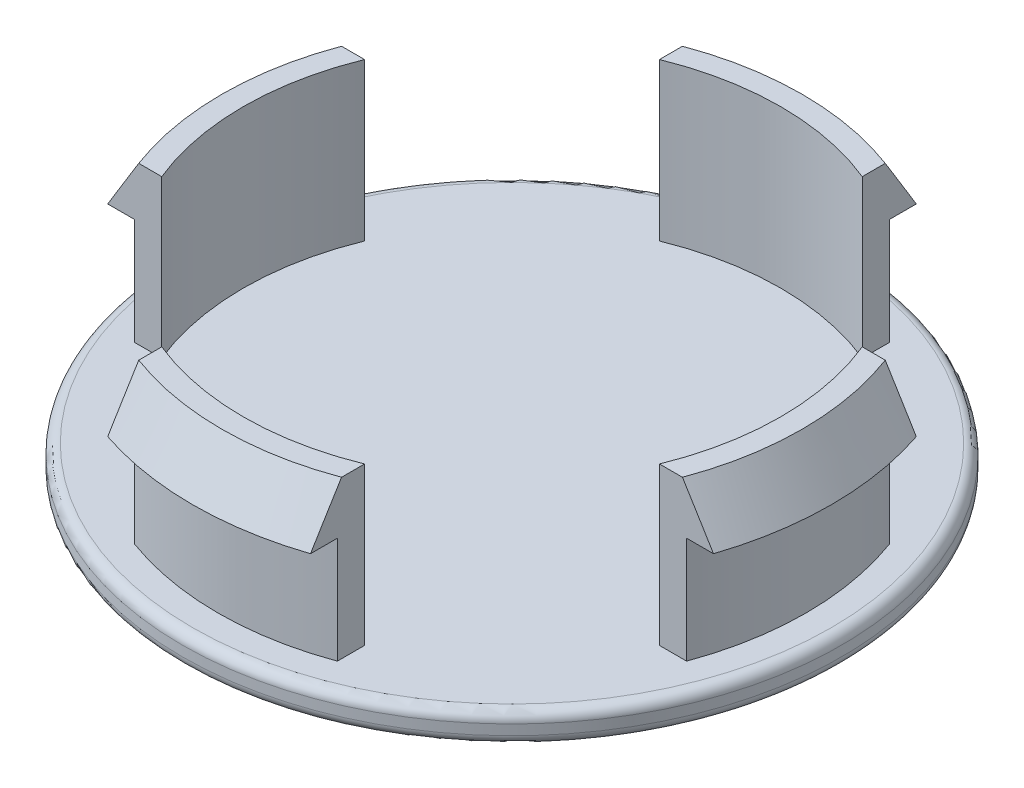
SolidWorks part; units mm, degrees
ref_plane "Спереди" through (0, 0, 0) normal (0, 0, 1) x (1, 0, 0)
ref_plane "Сверху" through (0, 0, 0) normal (0, 1, 0) x (1, 0, 0)
ref_plane "Справа" through (0, 0, 0) normal (1, 0, 0) x (0, 0, -1)
sketch "Эскиз3" plane through (0, 0, 0) normal (0, 0, 1) x (1, 0, 0)
  line L0 (0, 0) -> (0, 58.4773)
sketch "Эскиз1" plane through (0, 0, 0) normal (0, 0, 1) x (1, 0, 0)
  line L0 (0, 0) -> (0, -17.5509) construction
  line L1 (0, 0) -> (-31.5, 0)
  line L2 (-32.5, 1) -> (-32.5, 2)
  line L3 (-31.5, 3) -> (-29, 3)
  line L4 (-29, 3) -> (-29, 13.5)
  line L5 (-29, 13.5) -> (-31.5, 13.5)
  line L6 (-31.5, 13.5) -> (-28.6132, 18.5)
  line L7 (-28.6132, 18.5) -> (-26.5, 18.5)
  line L8 (-26.5, 18.5) -> (-26.5, 3)
  line L9 (-26.5, 3) -> (0, 3)
  line L10 (0, 3) -> (0, 0)
  arc A0 (-32.5, 1) -> (-31.5, 0) centre (-31.5, 1) ccw
  arc A1 (-32.5, 2) -> (-31.5, 3) centre (-31.5, 2) cw
  dimension "D10" = 1
  dimension "D11" = 1
  dimension "D1" = 65
  dimension "D2" = 58
  dimension "D3" = 63
  dimension "D4" = 3
  dimension "D5" = 3
  dimension "D6" = 5
  dimension "D7" = 5
  dimension "D8" = 10.5
  dimension "D9" = 60
revolve "Повернуть1" add sketch "Эскиз1" angle 360 about L0
sketch "Эскиз2" plane through (0, 18.5, 0) normal (0, 1, 0) x (1, 0, 0)
  line L0 (0, 0) -> (0, 37.57) construction
  line L1 (-10, 40.8566) -> (-10, 14.3515)
  line L2 (10, 40.8566) -> (10, 14.3515)
  line L3 (40.8566, 10) -> (14.3515, 10)
  line L4 (40.8566, -10) -> (14.3515, -10)
  line L5 (10, -40.8566) -> (10, -14.3515)
  line L6 (-10, -40.8566) -> (-10, -14.3515)
  line L7 (-40.8566, -10) -> (-14.3515, -10)
  line L8 (-40.8566, 10) -> (-14.3515, 10)
  circle A0 centre (0, 0) radius 17.4918
  circle A1 centre (0, 0) radius 42.0626
  point P24 (0, 0)
  circle M1 centre (0, 0) radius 28.6132
  circle M2 centre (0, 0) radius 26.5
  dimension "D1" = 20
  dimension "D2" = 4
extrude "Вырез-Вытянуть1" cut sketch "Эскиз2" against normal up to surface (15.5 mm away) contours L1 A1 L8 M1 | L3 L2 M1 M2 | L3 A1 L2 M1 | L5 A1 L4 M1 | L5 L4 M1 M2 | L7 A1 L6 M1 | L7 L6 M1 M2 | L8 L1 M1 M2 up to face at (0, 3, 31.5)
